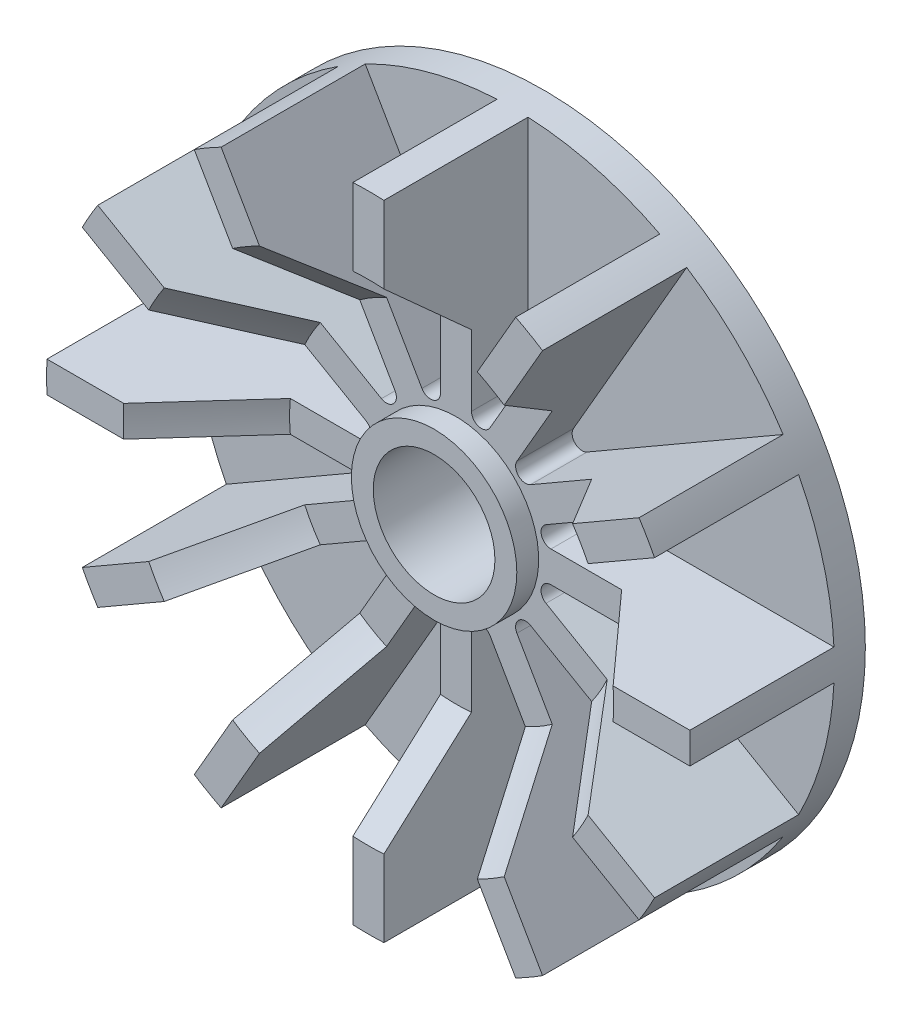
SolidWorks part; units mm, degrees
ref_plane "Front Plane" through (0, 0, 0) normal (0, 0, 1) x (1, 0, 0)
ref_plane "Top Plane" through (0, 0, 0) normal (0, 1, 0) x (1, 0, 0)
ref_plane "Right Plane" through (0, 0, 0) normal (1, 0, 0) x (0, 0, -1)
sketch "Sketch1" plane through (0, 0, 0) normal (0, 0, 1) x (1, 0, 0)
  line L0 (-2.9279, 8.3225) -> (2.9279, 8.3225)
  circle A0 centre (0, 0) radius 8.5725 construction
  arc A1 (-2.9279, 8.3225) -> (2.9279, 8.3225) centre (0, 0) ccw
  circle A2 centre (0, 0) radius 46.6725
  circle A4 centre (0, 0) radius 8.8225 construction
  point P8 (0, 8.8225)
  point P9 (9.0725, 0)
  dimension "D1" = 17.145
  dimension "D3" = 93.345
  dimension "D4" = 0.5
  dimension "D2" = 0.25
extrude "Boss-Extrude1" add sketch "Sketch1" along normal blind 4.5
sketch "Sketch2" plane through (0, 0, 4.5) normal (0, 0, 1) x (1, 0, 0)
  line L0 (-2.25, 46.6182) -> (-2.25, 13.7784)
  line L1 (0, 0) -> (0, 46.6725) construction
  line L2 (2.25, 46.6182) -> (2.25, 13.7784)
  line L3 (21.3606, 41.4976) -> (4.9406, 13.0574)
  line L4 (25.2577, 39.2476) -> (8.8377, 10.8074)
  line L5 (39.2476, 25.2577) -> (10.8074, 8.8377)
  line L6 (41.4976, 21.3606) -> (13.0574, 4.9406)
  line L7 (46.6182, 2.25) -> (13.7784, 2.25)
  line L8 (46.6182, -2.25) -> (13.7784, -2.25)
  line L9 (41.4976, -21.3606) -> (13.0574, -4.9406)
  line L10 (39.2476, -25.2577) -> (10.8074, -8.8377)
  line L11 (25.2577, -39.2476) -> (8.8377, -10.8074)
  line L12 (21.3606, -41.4976) -> (4.9406, -13.0574)
  line L13 (2.25, -46.6182) -> (2.25, -13.7784)
  line L14 (-2.25, -46.6182) -> (-2.25, -13.7784)
  line L15 (-21.3606, -41.4976) -> (-4.9406, -13.0574)
  line L16 (-25.2577, -39.2476) -> (-8.8377, -10.8074)
  line L17 (-39.2476, -25.2577) -> (-10.8074, -8.8377)
  line L18 (-41.4976, -21.3606) -> (-13.0574, -4.9406)
  line L19 (-46.6182, -2.25) -> (-13.7784, -2.25)
  line L20 (-46.6182, 2.25) -> (-13.7784, 2.25)
  line L21 (-41.4976, 21.3606) -> (-13.0574, 4.9406)
  line L22 (-39.2476, 25.2577) -> (-10.8074, 8.8377)
  line L23 (-25.2577, 39.2476) -> (-8.8377, 10.8074)
  line L24 (-21.3606, 41.4976) -> (-4.9406, 13.0574)
  line L25 (-2.25, 13.7784) -> (-4.9406, 13.0574) construction
  line L26 (-3.5953, 13.4179) -> (-12.0797, 45.0822) construction
  line L27 (-3.3187, -12.3856) -> (0, 0) construction
  line L28 (2.9279, 8.3225) -> (-2.9279, 8.3225) construction
  line L29 (2.9279, 8.3225) -> (-2.9279, 8.3225)
  arc A0 (-2.9279, 8.3225) -> (2.9279, 8.3225) centre (0, 0) ccw construction
  arc A1 (-2.9279, 8.3225) -> (2.9279, 8.3225) centre (0, 0) ccw construction
  arc A2 (-2.9279, 8.3225) -> (2.9279, 8.3225) centre (0, 0) ccw
  arc A4 (2.25, 46.6182) -> (-2.25, 46.6182) centre (0, 0) ccw
  circle A5 centre (0, 0) radius 46.6725 construction
  arc A6 (25.2577, 39.2476) -> (21.3606, 41.4976) centre (0, 0) ccw
  arc A7 (41.4976, 21.3606) -> (39.2476, 25.2577) centre (0, 0) ccw
  arc A8 (46.6182, -2.25) -> (46.6182, 2.25) centre (0, 0) ccw
  arc A9 (39.2476, -25.2577) -> (41.4976, -21.3606) centre (0, 0) ccw
  arc A10 (21.3606, -41.4976) -> (25.2577, -39.2476) centre (0, 0) ccw
  arc A11 (-2.25, -46.6182) -> (2.25, -46.6182) centre (0, 0) ccw
  arc A12 (-25.2577, -39.2476) -> (-21.3606, -41.4976) centre (0, 0) ccw
  arc A13 (-41.4976, -21.3606) -> (-39.2476, -25.2577) centre (0, 0) ccw
  arc A14 (-46.6182, 2.25) -> (-46.6182, -2.25) centre (0, 0) ccw
  arc A15 (-39.2476, 25.2577) -> (-41.4976, 21.3606) centre (0, 0) ccw
  arc A16 (-21.3606, 41.4976) -> (-25.2577, 39.2476) centre (0, 0) ccw
  arc A17 (-2.25, 13.7784) -> (-4.9406, 13.0574) centre (-3.6919, 13.7784) cw
  arc A18 (4.9406, 13.0574) -> (2.25, 13.7784) centre (3.6919, 13.7784) cw
  arc A19 (10.8074, 8.8377) -> (8.8377, 10.8074) centre (10.0865, 10.0865) cw
  arc A20 (13.7784, 2.25) -> (13.0574, 4.9406) centre (13.7784, 3.6919) cw
  arc A21 (13.0574, -4.9406) -> (13.7784, -2.25) centre (13.7784, -3.6919) cw
  arc A22 (8.8377, -10.8074) -> (10.8074, -8.8377) centre (10.0865, -10.0865) cw
  arc A23 (2.25, -13.7784) -> (4.9406, -13.0574) centre (3.6919, -13.7784) cw
  arc A24 (-4.9406, -13.0574) -> (-2.25, -13.7784) centre (-3.6919, -13.7784) cw
  arc A25 (-10.8074, -8.8377) -> (-8.8377, -10.8074) centre (-10.0865, -10.0865) cw
  arc A26 (-13.7784, -2.25) -> (-13.0574, -4.9406) centre (-13.7784, -3.6919) cw
  arc A27 (-13.0574, 4.9406) -> (-13.7784, 2.25) centre (-13.7784, 3.6919) cw
  arc A28 (-8.8377, 10.8074) -> (-10.8074, 8.8377) centre (-10.0865, 10.0865) cw
  point P60 (-3.3187, -12.3856)
  point P62 (-2.2834, -8.5219)
  circle M51 centre (0, 0) radius 46.6725
  arc M53 (2.9279, 8.3225) -> (-2.9279, 8.3225) centre (0, 0) cw
  dimension "D1" = 4.5
  dimension "D4" = 4
  dimension "D2" = 12
  dimension "D3" = 12
extrude "Boss-Extrude2" add sketch "Sketch2" along normal blind 25.4 from surface at -4.5 contours L23 A28 L22 L21 A27 L20 L19 A26 L18 L17 A25 L16 L15 A24 L14 L13 A23 L12 L11 A22 L10 L9 A21 L8 L7 A20 L6 L5 A19 L4 L3 A18 L2 L0 A17 L24 A2 M51 M53 starting at face at (46.6725, 0, 0)
sketch "Sketch3" plane through (0, 0, 0) normal (0, 1, 0) x (1, 0, 0)
  line L0 (0, 0) -> (0, -25.4) construction
  line L1 (-8.8225, -25.4) -> (8.8225, -25.4) construction
  line L2 (-24.13, -25.4) -> (24.13, -25.4) construction
  line L3 (46.6182, -25.4) -> (13.7784, -25.4) construction
  line L4 (-24.13, -12.7) -> (-6.35, -12.7)
  line L5 (-24.13, -12.7) -> (-35.56, -25.4)
  line L6 (-46.6182, -25.4) -> (-13.7784, -25.4) construction
  line L7 (-35.56, -25.4) -> (-6.35, -25.4)
  line L9 (-24.13, -12.7) -> (24.13, -12.7) construction
  line L11 (-6.35, -12.7) -> (-6.35, -25.4)
  point P9 (0, -25.4)
  dimension "D1" = 48.26
  dimension "D3" = 11.43
  dimension "D4" = 12.7
  dimension "D2" = 12.7
revolve "Cut-Revolve1" cut sketch "Sketch3" angle 360 about L0
sketch "Sketch4" plane through (0, 0, 12.7) normal (0, 0, 1) x (1, 0, 0)
  circle A0 centre (0, 0) radius 8.8225
  arc A1 (-2.9279, 8.3225) -> (2.9279, 8.3225) centre (0, 0) ccw construction
  circle A2 centre (0, 0) radius 11.9975
  dimension "D1" = 3.175
extrude "Boss-Extrude3" add sketch "Sketch4" along normal blind 3.175
